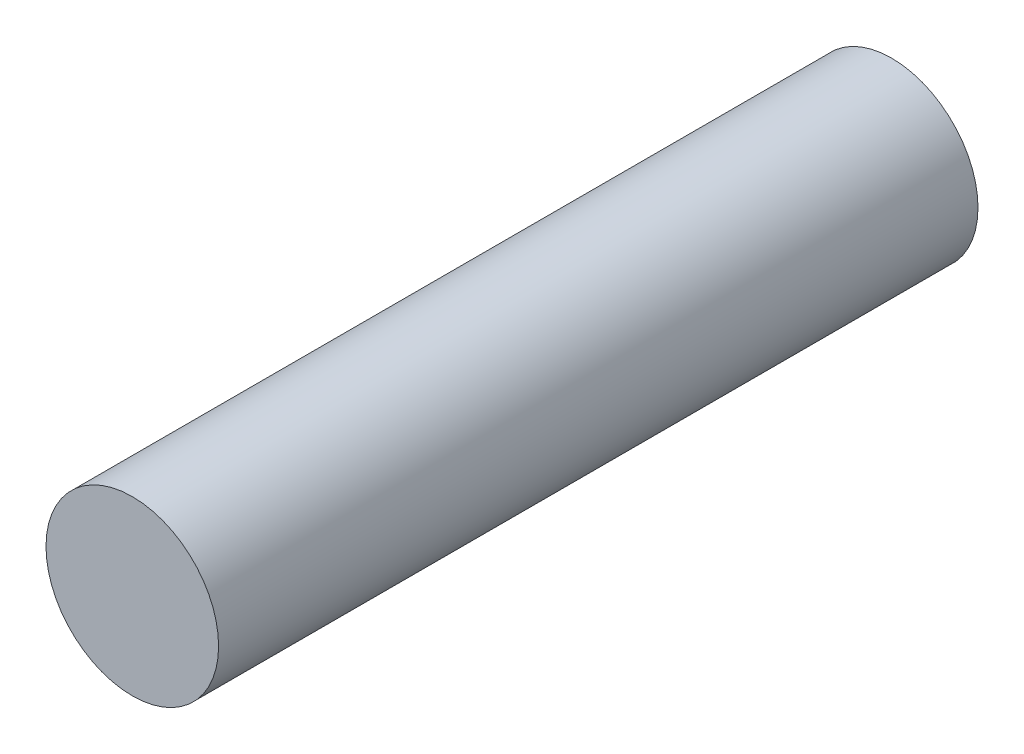
SolidWorks part; units mm, degrees
ref_plane "Plan de face" through (0, 0, 0) normal (0, 0, 1) x (1, 0, 0)
ref_plane "Plan de dessus" through (0, 0, 0) normal (0, 1, 0) x (1, 0, 0)
ref_plane "Plan de droite" through (0, 0, 0) normal (1, 0, 0) x (0, 0, -1)
sketch "Esquisse1" plane through (0, 0, 0) normal (0, 0, 1) x (1, 0, 0)
  circle A0 centre (0, 0) radius 2.5
  dimension "D1" = 5
extrude "Boss.-Extru.1" add sketch "Esquisse1" along normal blind 22
